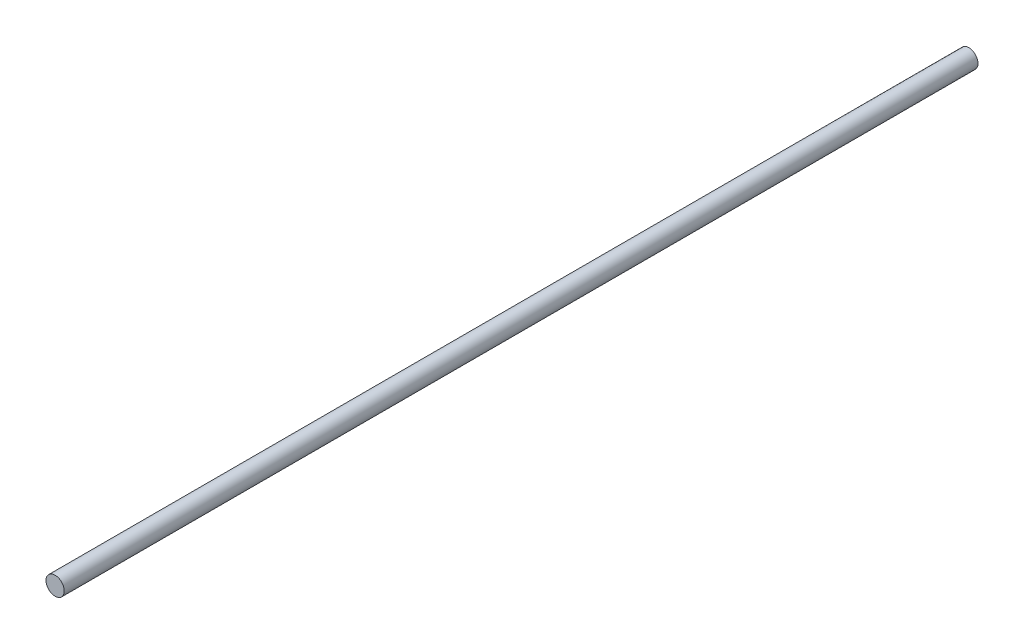
SolidWorks part; units mm, degrees
material "Stainless Steel (ferritic)"
ref_plane "Ön Düzlem" through (0, 0, 0) normal (0, 0, 1) x (1, 0, 0)
ref_plane "Üst Düzlem" through (0, 0, 0) normal (0, 1, 0) x (1, 0, 0)
ref_plane "Sağ Düzlem" through (0, 0, 0) normal (1, 0, 0) x (0, 0, -1)
sketch "Çizim1" plane through (0, 0, 0) normal (0, 0, 1) x (1, 0, 0)
  circle A0 centre (0, 0) radius 4
  dimension "D1" = 8
extrude "Yükseklik-Ekstrüzyon1" add sketch "Çizim1" along normal blind 400
